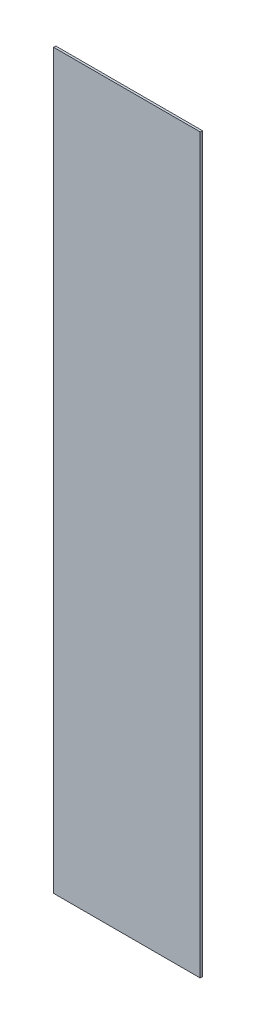
SolidWorks part; units mm, degrees
ref_plane "Front Plane" through (0, 0, 0) normal (0, 0, 1) x (1, 0, 0)
ref_plane "Top Plane" through (0, 0, 0) normal (0, 1, 0) x (1, 0, 0)
ref_plane "Right Plane" through (0, 0, 0) normal (1, 0, 0) x (0, 0, -1)
sketch "Sketch1" plane through (0, 0, 0) normal (0, 1, 0) x (1, 0, 0)
  line L1 (-12.7, 0.1905) -> (12.7, 0.1905)
  line L2 (-12.7, 0.1905) -> (-12.7, -0.1905)
  line L3 (-12.7, -0.1905) -> (12.7, -0.1905)
  line L4 (12.7, 0.1905) -> (12.7, -0.1905)
  line L5 (-12.7, 0.1905) -> (12.7, -0.1905) construction
  line L6 (-12.7, -0.1905) -> (12.7, 0.1905) construction
  point P0 (0, 0)
  dimension "D1" = 0.381
  dimension "D2" = 25.4
extrude "Boss-Extrude1" add sketch "Sketch1" along normal mid plane 127
